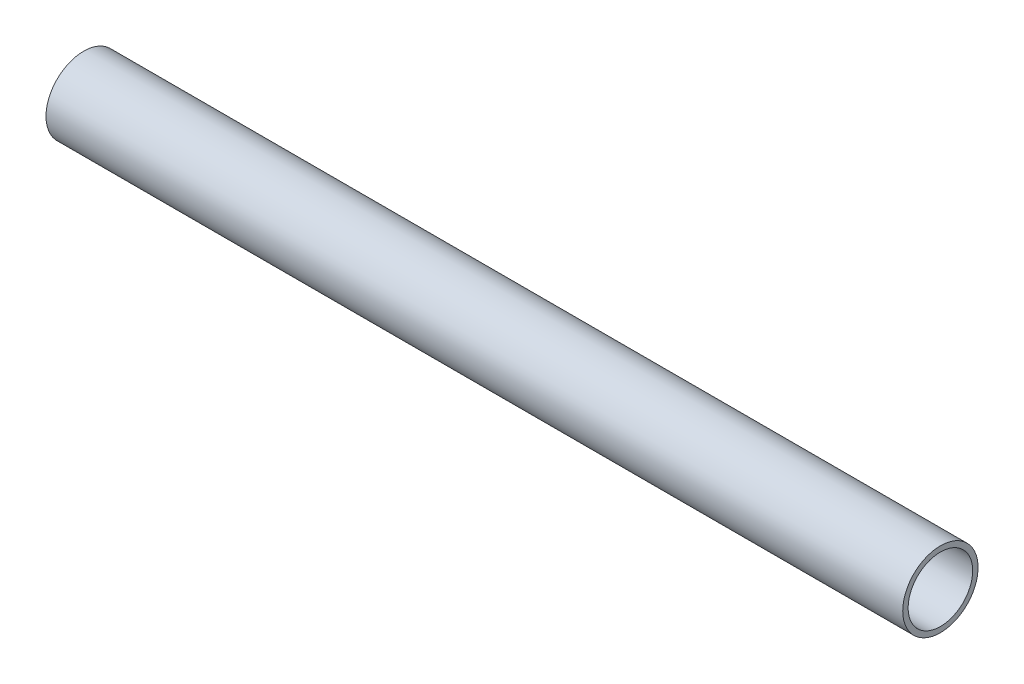
SolidWorks part; units mm, degrees
material "Carbon Pipe"
ref_plane "Ön Düzlem" through (0, 0, 0) normal (0, 0, 1) x (1, 0, 0)
ref_plane "Üst Düzlem" through (0, 0, 0) normal (0, 1, 0) x (1, 0, 0)
ref_plane "Sağ Düzlem" through (0, 0, 0) normal (1, 0, 0) x (0, 0, -1)
sketch "Çizim1" plane through (0, 0, 0) normal (1, 0, 0) x (0, 0, -1)
  circle A0 centre (0, 0) radius 7
  circle A1 centre (0, 0) radius 6
  dimension "D1" = 14
  dimension "D2" = 12
extrude "Yükseklik-Ekstrüzyon1" add sketch "Çizim1" along normal mid plane 159.2
